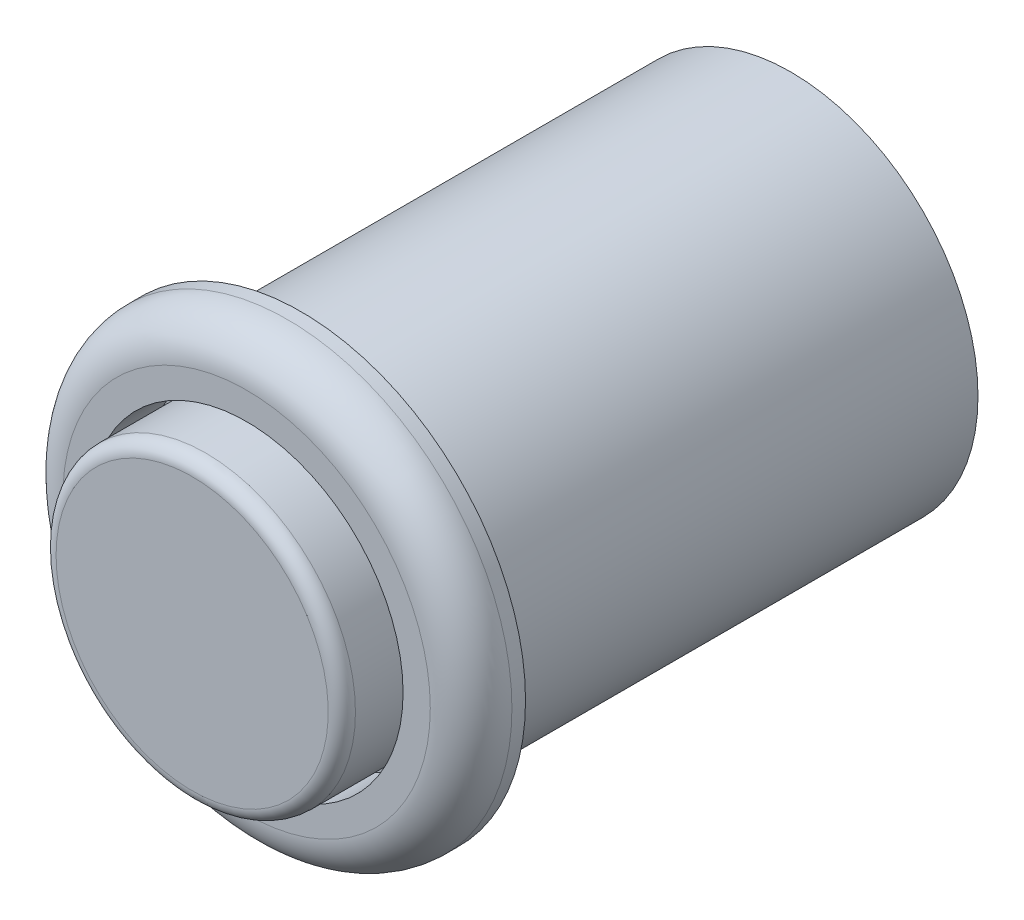
SolidWorks part; units mm, degrees
ref_plane "Plan de face" through (0, 0, 0) normal (0, 0, 1) x (1, 0, 0)
ref_plane "Plan de dessus" through (0, 0, 0) normal (0, 1, 0) x (1, 0, 0)
ref_plane "Plan de droite" through (0, 0, 0) normal (1, 0, 0) x (0, 0, -1)
sketch "Esquisse1" plane through (0, 0, 0) normal (0, 0, 1) x (1, 0, 0)
  circle A0 centre (0, 0) radius 16.5
  circle A1 centre (0, 0) radius 11.5
  dimension "D1" = 33
  dimension "D2" = 23
extrude "Boss.-Extru.1" add sketch "Esquisse1" along normal blind 4
fillet "Congé1" radius 3 1 edges at (16.5, 0, 4)
sketch "Esquisse2" plane through (0, 0, 0) normal (0, 0, -1) x (-1, 0, 0)
  circle A0 centre (0, 0) radius 11
  dimension "D1" = 22
extrude "Boss.-Extru.2" add sketch "Esquisse2" against normal blind 8 separate body
fillet "Congé2" radius 1 1 edges at (-11, 0, 8)
sketch "Esquisse3" plane through (0, 0, 0) normal (0, 0, -1) x (-1, 0, 0)
  circle A0 centre (0, 0) radius 13.75
  dimension "D1" = 27.5
extrude "Boss.-Extru.3" add sketch "Esquisse3" along normal blind 36
